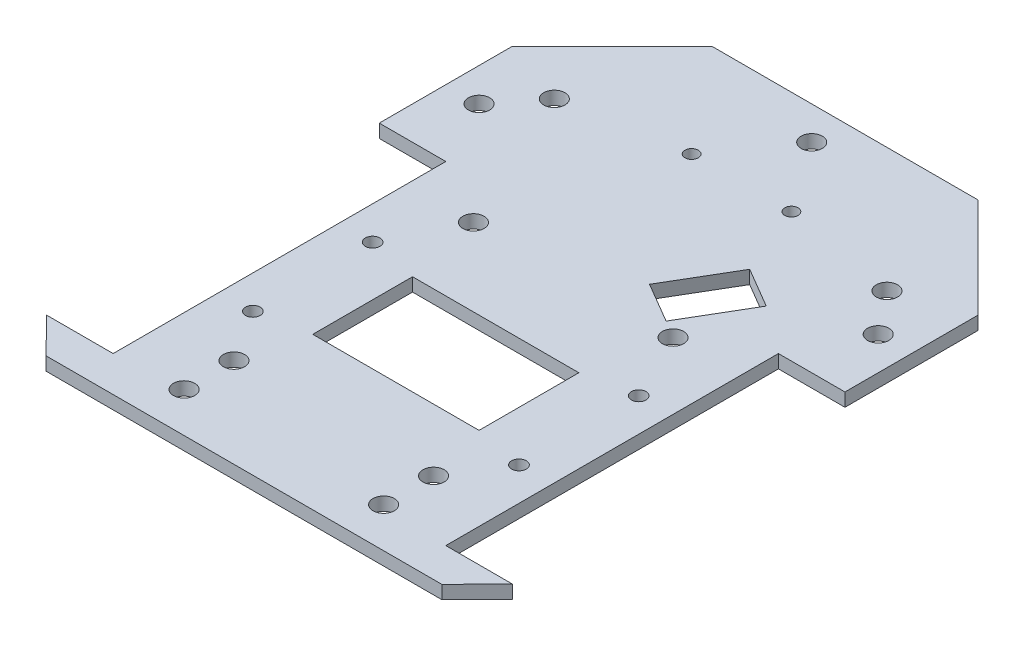
SolidWorks part; units mm, degrees
ref_plane "Front Plane" through (0, 0, 0) normal (0, 0, 1) x (1, 0, 0)
ref_plane "Top Plane" through (0, 0, 0) normal (0, 1, 0) x (1, 0, 0)
ref_plane "Right Plane" through (0, 0, 0) normal (1, 0, 0) x (0, 0, -1)
sketch "Sketch1" plane through (0, 0, 0) normal (0, 1, 0) x (1, 0, 0)
  line L0 (0, 46.5868) -> (0, -43.7554) construction
  line L1 (-20, 46.5868) -> (20, 46.5868)
  line L2 (-35, 31.5868) -> (-35, 11.5868)
  line L3 (-29.7546, -43.7554) -> (29.7546, -43.7554)
  line L4 (35, 31.5868) -> (35, 11.5868)
  line L5 (-28.4375, 38.1493) -> (31.3814, -42.0986) construction
  line L6 (-32.2499, -41.2141) -> (29.2309, 37.3559) construction
  line L7 (-35, 11.5868) -> (-25, 11.5868)
  line L8 (-35, 31.5868) -> (-20, 46.5868)
  line L9 (-25, 11.5868) -> (-25, -38.4132)
  line L10 (-25, -38.4132) -> (-35, -38.4132)
  line L11 (-35, -38.4132) -> (-29.7546, -43.7554)
  line L12 (35, -38.4132) -> (29.7546, -43.7554)
  line L13 (25, -38.4132) -> (35, -38.4132)
  line L14 (25, 11.5868) -> (25, -38.4132)
  line L15 (35, 11.5868) -> (25, 11.5868)
  line L16 (35, 31.5868) -> (20, 46.5868)
  line L18 (-25, -13.4132) -> (25, -13.4132) construction
  line L19 (12.3307, 7.3687) -> (17.9057, 16.8513)
  line L26 (-12.5, -5.9132) -> (12.5, -5.9132)
  line L27 (-12.5, -5.9132) -> (-12.5, -20.9132)
  line L28 (-12.5, -20.9132) -> (12.5, -20.9132)
  line L29 (12.5, -5.9132) -> (12.5, -20.9132)
  line L30 (-12.5, -5.9132) -> (12.5, -20.9132) construction
  line L31 (-12.5, -20.9132) -> (12.5, -5.9132) construction
  line L36 (17.9057, 16.8513) -> (11.8714, 20.399)
  line L37 (11.8714, 20.399) -> (6.2963, 10.9165)
  line L38 (6.2963, 10.9165) -> (12.3307, 7.3687)
  circle A0 centre (-30, 21.5868) radius 1.6
  circle A1 centre (30, 21.5868) radius 1.6
  circle A2 centre (0, 41.5868) radius 1.6
  circle A3 centre (-20, -4.4132) radius 1.1
  circle A4 centre (-20, -22.4132) radius 1.1
  circle A5 centre (20, -4.4132) radius 1.1
  circle A6 centre (20, -22.4132) radius 1.1
  circle A10 centre (-15, -37.7554) radius 1.6
  circle A11 centre (15, -37.7554) radius 1.6
  circle A14 centre (-15, 5.7446) radius 1.6
  circle A15 centre (15, 5.7446) radius 1.6
  circle A16 centre (-15, -30.2554) radius 1.6
  circle A17 centre (15, -30.2554) radius 1.6
  point P0 (0, 0)
  point P54 (0, -13.4132)
  dimension "D1" = 10
  dimension "D2" = 5
  dimension "D6" = 3.2
  dimension "D8" = 3.2
  dimension "D9" = 5
  dimension "D10" = 2.2
  dimension "D11" = 9
  dimension "D12" = 5
  dimension "D17" = 3.2
  dimension "D18" = 6
  dimension "D19" = 10
  dimension "D22" = 3.2
  dimension "D23" = 3.2
  dimension "D24" = 13.5
  dimension "D25" = 36
  dimension "D3" = 10
  dimension "D4" = 35
  dimension "D5" = 20
  dimension "D7" = 50
  dimension "D20" = 25
  dimension "D21" = 15
  dimension "D28" = 7
  dimension "D29" = 6.0344
  dimension "D30" = 11
extrude "Boss-Extrude1" add sketch "Sketch1" along normal blind 2
sketch "Sketch2" plane through (0, 2, 0) normal (0, 1, 0) x (1, 0, 0)
  line L0 (-25, 42.7251) -> (-25, 7.7251) construction
  line L1 (0, 46.5868) -> (0, 9.5734) construction
  line L2 (20, 46.5868) -> (-20, 46.5868) construction
  circle A0 centre (-25, 27.9006) radius 1.6
  circle A1 centre (25, 27.9006) radius 1.6
  dimension "D1" = 3.2
extrude "Cut-Extrude1" cut sketch "Sketch2" against normal blind 15
sketch "Sketch3" plane through (0, 2, 0) normal (0, 1, 0) x (1, 0, 0)
  line L0 (0, 46.5868) -> (0, 10.4292) construction
  line L1 (20, 46.5868) -> (-20, 46.5868) construction
  circle A0 centre (-7.5, 31.0383) radius 1
  circle A1 centre (7.5, 31.0383) radius 1
  dimension "D1" = 15
  dimension "D2" = 2
extrude "Cut-Extrude2" cut sketch "Sketch3" against normal through all
